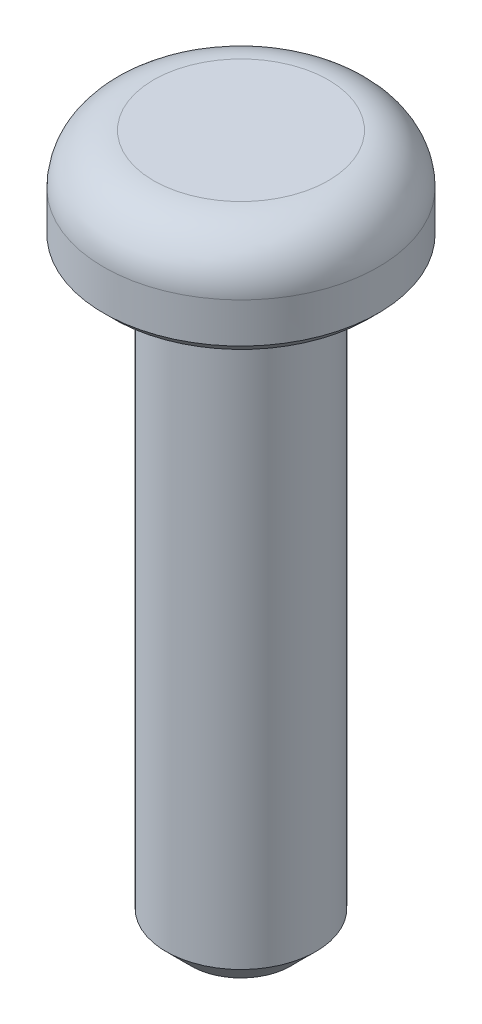
SolidWorks part; units mm, degrees
ref_plane "Front Plane" through (0, 0, 0) normal (0, 0, 1) x (1, 0, 0)
ref_plane "Top Plane" through (0, 0, 0) normal (0, 1, 0) x (1, 0, 0)
ref_plane "Right Plane" through (0, 0, 0) normal (1, 0, 0) x (0, 0, -1)
sketch "Sketch1" plane through (0, 0, 0) normal (0, 0, 1) x (1, 0, 0)
  line L0 (0, 0) -> (0, 14)
  line L1 (0, 14) -> (2.75, 14)
  line L2 (2.75, 14) -> (2.75, 12)
  line L3 (2.75, 12) -> (1.5, 12)
  line L4 (1.5, 12) -> (1.5, 0)
  line L5 (1.5, 0) -> (0, 0)
  dimension "D1" = 1.5
  dimension "D2" = 2.75
  dimension "D3" = 2
  dimension "D4" = 12
revolve "Revolve1" add sketch "Sketch1" angle 360 about L0
fillet "Fillet1" radius 1 1 edges at (0, 14, -2.75)
chamfer "Chamfer1" distance 0.5 angle 45 1 edges at (0, 0, -1.5)
chamfer "Chamfer2" distance 0.2 angle 45 1 edges at (0, 12, -2.75)
